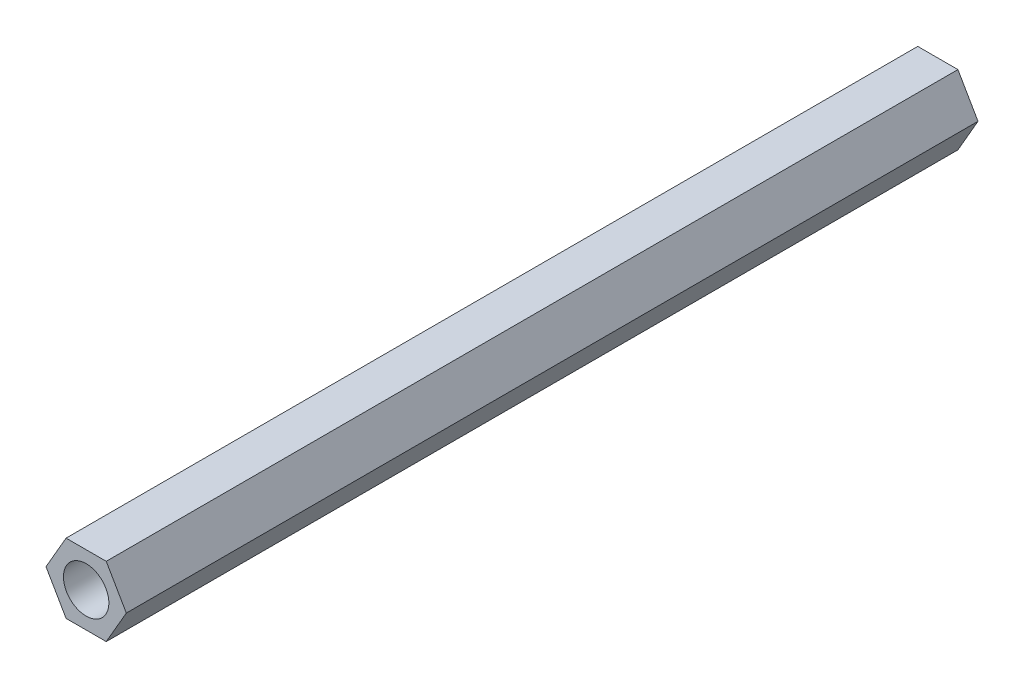
SolidWorks part; units mm, degrees
material "黄铜"
ref_plane "前视基准面" through (0, 0, 0) normal (0, 0, 1) x (1, 0, 0)
ref_plane "上视基准面" through (0, 0, 0) normal (0, 1, 0) x (1, 0, 0)
ref_plane "右视基准面" through (0, 0, 0) normal (1, 0, 0) x (0, 0, -1)
sketch "草图1" plane through (0, 0, 0) normal (0, 0, 1) x (1, 0, 0)
  line L1 (2.829, 0) -> (1.4145, 2.45)
  line L2 (1.4145, 2.45) -> (-1.4145, 2.45)
  line L3 (-1.4145, 2.45) -> (-2.829, 0)
  line L4 (-2.829, 0) -> (-1.4145, -2.45)
  line L5 (-1.4145, -2.45) -> (1.4145, -2.45)
  line L6 (1.4145, -2.45) -> (2.829, 0)
  circle A0 centre (0, 0) radius 1.6
  circle A1 centre (0, 0) radius 2.45 construction
  dimension "D1" = 3.2
  dimension "D2" = 4.9
extrude "凸台-拉伸1" add sketch "草图1" along normal blind 60
